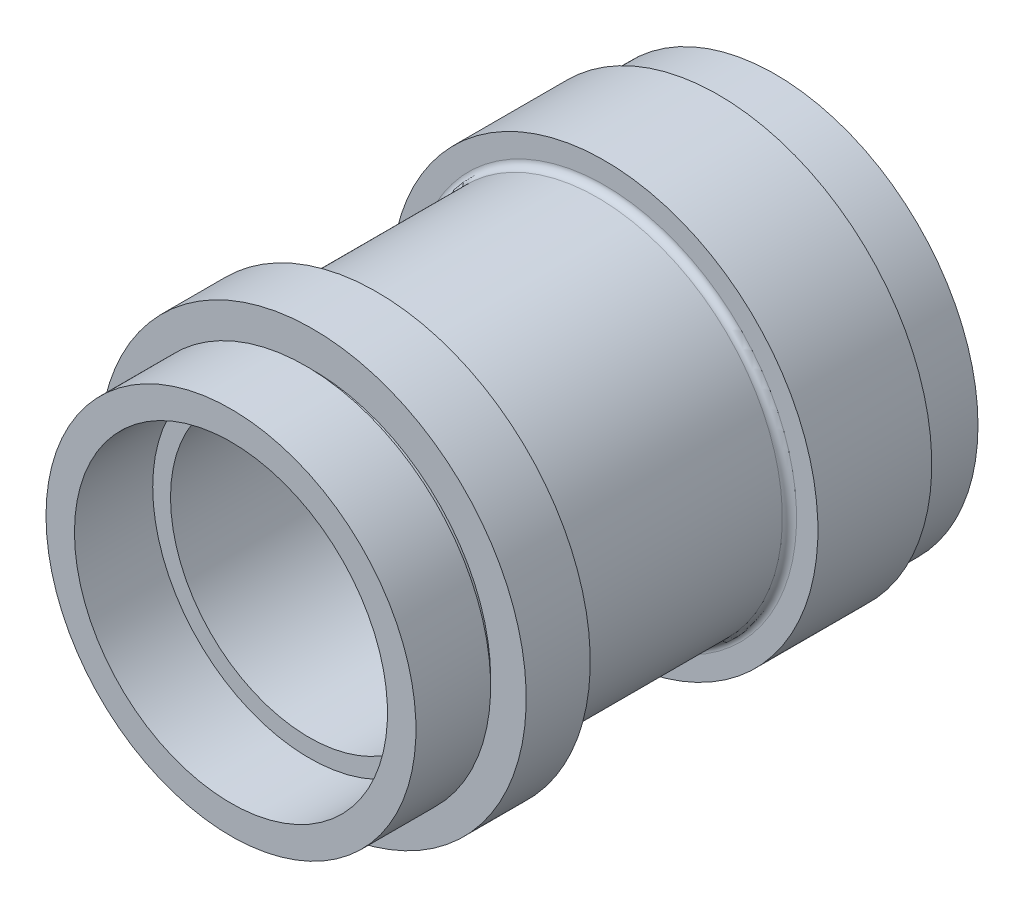
SolidWorks part; units mm, degrees
material "Alliage de zinc AC41A, brut"
ref_plane "Plan de face" through (0, 0, 0) normal (0, 0, 1) x (1, 0, 0)
ref_plane "Plan de dessus" through (0, 0, 0) normal (0, 1, 0) x (1, 0, 0)
ref_plane "Plan de droite" through (0, 0, 0) normal (1, 0, 0) x (0, 0, -1)
sketch "Esquisse1" plane through (0, 0, 0) normal (0, 0, 1) x (1, 0, 0)
  circle A0 centre (0, 0) radius 14.25
  dimension "D1" = 28.5
extrude "Boss.-Extru.1" add sketch "Esquisse1" along normal blind 4
sketch "Esquisse2" plane through (0, 0, 4) normal (0, 0, 1) x (1, 0, 0)
  circle A0 centre (0, 0) radius 15
  dimension "D1" = 30
extrude "Boss.-Extru.2" add sketch "Esquisse2" along normal blind 28.5
sketch "Esquisse3" plane through (0, 0, 32.5) normal (0, 0, 1) x (1, 0, 0)
  circle A0 centre (0, 0) radius 12.5
  dimension "D1" = 25
extrude "Boss.-Extru.3" add sketch "Esquisse3" along normal blind 0.5
sketch "Esquisse4" plane through (0, 0, 33) normal (0, 0, 1) x (1, 0, 0)
  circle A0 centre (0, 0) radius 13
  dimension "D1" = 26
extrude "Boss.-Extru.4" add sketch "Esquisse4" along normal blind 5.25
cosmetic thread "Représentation de filetage1" parameters "D2"=25
sketch "Esquisse5" plane through (0, 0, 0) normal (1, 0, 0) x (0, 0, -1)
  line L0 (0, 0) -> (-38.25, 0)
  line L1 (-38.25, 13) -> (-38.25, -13) construction
  line L2 (-32.75, 9.75) -> (-32.75, 11)
  line L4 (0, 0) -> (0, 9.75)
  line L5 (0, 9.75) -> (-32.75, 9.75)
  line L7 (-32.75, 11) -> (-38.25, 11)
  line L8 (-38.25, 11) -> (-38.25, 0)
  line L10 (-28, 15) -> (-12, 15)
  line L11 (-28, 15) -> (-28, 13.5)
  line L12 (-27.5, 13) -> (-12.5, 13)
  line L13 (-12, 15) -> (-12, 13.5)
  line L14 (-32.5, 15) -> (-32.5, -15) construction
  arc A0 (-12.5, 13) -> (-12, 13.5) centre (-12.5, 13.5) ccw
  arc A1 (-27.5, 13) -> (-28, 13.5) centre (-27.5, 13.5) cw
  point P26 (-28, 13)
  dimension "D7" = 0.5
  dimension "D1" = 9.75
  dimension "D2" = 32.75
  dimension "D3" = 4.5
  dimension "D4" = 1.25
  dimension "D5" = 16
  dimension "D6" = 2
revolve "Enlèvement de matière-Révolution1" cut sketch "Esquisse5" angle 360 about L0
sketch "Esquisse11" plane through (0, 0, 0) normal (0, 0, -1) x (-1, 0, 0)
  line L1 (0, 12.75) -> (0, 14.25) construction
  circle A0 centre (0, 0) radius 14.25 construction
  circle A1 centre (0, 0) radius 14.25 construction
  point P2 (0, 12.75)
  point P12 (0, 12.75)
  dimension "D1" = 1.5
hole_wizard "Diamètre du perçage Ø2.0 (2)1" positions "Esquisse11" profile "Esquisse10" hole size "Ø2.0" standard "ISO"
sketch "Esquisse10" plane through (0, 12.75, 0) normal (1, 0, 0) x (0, 1, 0)
  line L0 (0, 0) -> (0, 9.6009)
  line L1 (0, 9.6009) -> (1, 9)
  line L2 (1, 9) -> (1, 0)
  line L5 (1, 0) -> (0, 0)
  line L10 (0, 9.6009) -> (-1, 9) construction
  line L11 (0, -6.35) -> (0, 107.95) construction
  dimension "Diamètre du perçage" = 2
  dimension "Profondeur du perçage" = 9
  dimension "Angle de pointe" = 118
